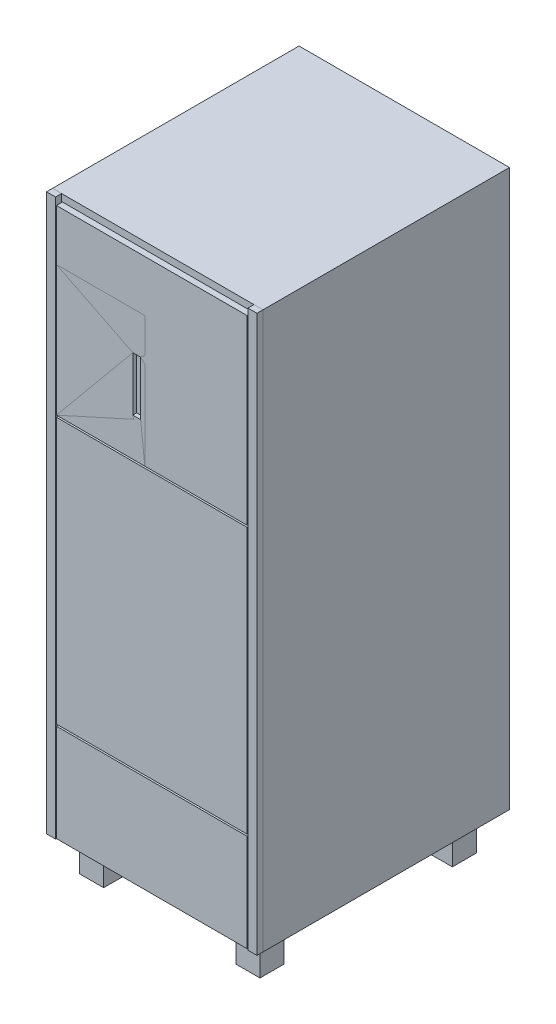
SolidWorks part; units mm, degrees
ref_plane "Front Plane" through (0, 0, 0) normal (0, 0, 1) x (1, 0, 0)
ref_plane "Top Plane" through (0, 0, 0) normal (0, 1, 0) x (1, 0, 0)
ref_plane "Right Plane" through (0, 0, 0) normal (1, 0, 0) x (0, 0, -1)
other "Configuration Table"
sketch "Sketch1" plane through (0, 0, 0) normal (0, 0, 1) x (1, 0, 0)
  line L1 (0, 120) -> (700, 120)
  line L2 (0, 120) -> (0, 1970)
  line L3 (0, 1970) -> (700, 1970)
  line L4 (700, 120) -> (700, 1970)
extrude "govde_kasa" add sketch "Sketch1" against normal blind 820 separate body
sketch "Sketch2" plane through (0, 0, 0) normal (0, 1, 0) x (1, 0, 0)
  line L1 (50, 40) -> (130, 40)
  line L2 (50, 40) -> (50, 120)
  line L3 (50, 120) -> (130, 120)
  line L4 (130, 40) -> (130, 120)
extrude "ayak_1" add sketch "Sketch2" along normal blind 120 separate body
sketch "Sketch3" plane through (0, 0, 0) normal (0, 1, 0) x (1, 0, 0)
  line L1 (570, 40) -> (650, 40)
  line L2 (570, 40) -> (570, 120)
  line L3 (570, 120) -> (650, 120)
  line L4 (650, 40) -> (650, 120)
extrude "ayak_2" add sketch "Sketch3" along normal blind 120 separate body
sketch "Sketch4" plane through (0, 0, 0) normal (0, 1, 0) x (1, 0, 0)
  line L1 (50, 680) -> (130, 680)
  line L2 (50, 680) -> (50, 760)
  line L3 (50, 760) -> (130, 760)
  line L4 (130, 680) -> (130, 760)
extrude "ayak_3" add sketch "Sketch4" along normal blind 120 separate body
sketch "Sketch5" plane through (0, 0, 0) normal (0, 1, 0) x (1, 0, 0)
  line L1 (570, 680) -> (650, 680)
  line L2 (570, 680) -> (570, 760)
  line L3 (570, 760) -> (650, 760)
  line L4 (650, 680) -> (650, 760)
extrude "ayak_4" add sketch "Sketch5" along normal blind 120 separate body
sketch "Sketch6" plane through (0, 0, 0) normal (0, 0, 1) x (1, 0, 0)
  line L1 (0, 120) -> (30, 120)
  line L2 (0, 120) -> (0, 1970)
  line L3 (0, 1970) -> (30, 1970)
  line L4 (30, 120) -> (30, 1970)
extrude "sove_sol" add sketch "Sketch6" along normal blind 20 separate body
sketch "Sketch7" plane through (0, 0, 0) normal (0, 0, 1) x (1, 0, 0)
  line L1 (670, 120) -> (700, 120)
  line L2 (670, 120) -> (670, 1970)
  line L3 (670, 1970) -> (700, 1970)
  line L4 (700, 120) -> (700, 1970)
extrude "sove_sag" add sketch "Sketch7" along normal blind 20 separate body
sketch "Sketch8" plane through (0, 0, 0) normal (0, 0, 1) x (1, 0, 0)
  line L1 (33, 1343) -> (667, 1343)
  line L2 (33, 1343) -> (33, 1947)
  line L3 (33, 1947) -> (667, 1947)
  line L4 (667, 1343) -> (667, 1947)
extrude "panel_ust" add sketch "Sketch8" along normal blind 20 separate body
sketch "Sketch9" plane through (0, 0, 0) normal (0, 0, 1) x (1, 0, 0)
  line L1 (33, 1343) -> (327, 1343)
  line L2 (33, 1343) -> (33, 1777)
  line L3 (33, 1777) -> (327, 1777)
  line L4 (327, 1343) -> (327, 1777)
extrude "kapak_pano_ust" add sketch "Sketch9" along normal blind 20 separate body
sketch "Sketch10" plane through (0, 0, 0) normal (0, 0, 1) x (1, 0, 0)
  line L1 (287, 1470) -> (313, 1470)
  line L2 (287, 1470) -> (287, 1650)
  line L3 (287, 1650) -> (313, 1650)
  line L4 (313, 1470) -> (313, 1650)
extrude "kapak_pano_ust_kulp" cut sketch "Sketch10" along normal blind 13 from offset 7
sketch "Sketch11" plane through (0, 0, 0) normal (0, 0, 1) x (1, 0, 0)
  line L1 (33, 453) -> (667, 453)
  line L2 (33, 453) -> (33, 1337)
  line L3 (33, 1337) -> (667, 1337)
  line L4 (667, 453) -> (667, 1337)
extrude "panel_orta" add sketch "Sketch11" along normal blind 20 separate body
sketch "Sketch12" plane through (0, 0, 0) normal (0, 0, 1) x (1, 0, 0)
  line L1 (103, 723) -> (597, 723)
  line L2 (103, 723) -> (103, 1077)
  line L3 (103, 1077) -> (597, 1077)
  line L4 (597, 723) -> (597, 1077)
extrude "aciklik_tepsi" cut sketch "Sketch12" against normal blind 100
sketch "Sketch13" plane through (0, 0, 0) normal (0, 0, 1) x (1, 0, 0)
  line L1 (33, 123) -> (667, 123)
  line L2 (33, 123) -> (33, 447)
  line L3 (33, 447) -> (667, 447)
  line L4 (667, 123) -> (667, 447)
extrude "panel_alt" add sketch "Sketch13" along normal blind 20 separate body
